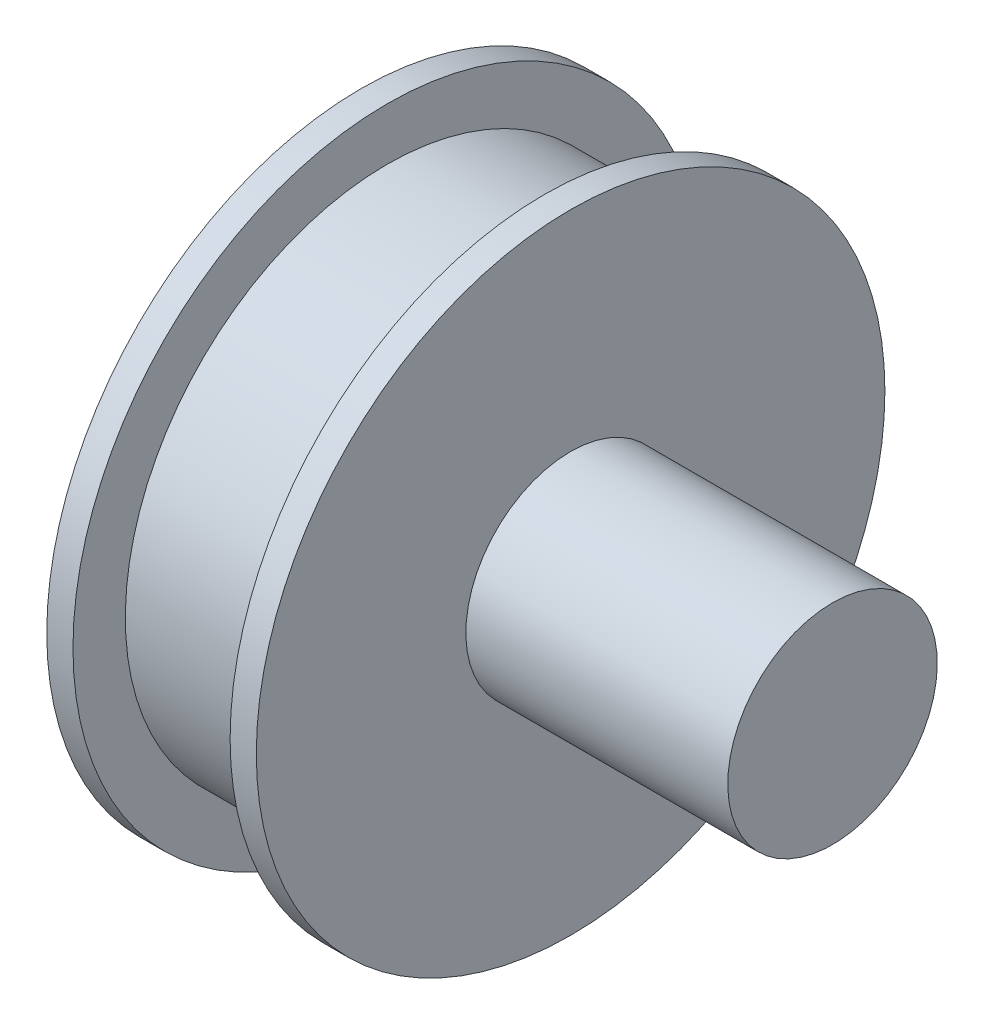
SolidWorks part; units mm, degrees
material "Plain Carbon Steel"
ref_plane "Front Plane" through (0, 0, 0) normal (0, 0, 1) x (1, 0, 0)
ref_plane "Top Plane" through (0, 0, 0) normal (0, 1, 0) x (1, 0, 0)
ref_plane "Right Plane" through (0, 0, 0) normal (1, 0, 0) x (0, 0, -1)
sketch "Sketch1" plane through (0, 0, 0) normal (0, 0, 1) x (1, 0, 0)
  line L0 (0, 5) -> (0, 30)
  line L1 (0, 30) -> (2.5, 30)
  line L2 (2.5, 30) -> (2.5, 25)
  line L3 (2.5, 25) -> (17.5, 25)
  line L4 (17.5, 25) -> (17.5, 30)
  line L5 (17.5, 30) -> (20, 30)
  line L6 (20, 30) -> (20, 10)
  line L7 (20, 10) -> (45, 10)
  line L8 (45, 10) -> (45, 0)
  line L9 (45, 0) -> (5, 0)
  line L10 (0, 5) -> (5, 5)
  line L11 (5, 5) -> (5, 0)
  point P0 (0, 0)
  dimension "D2" = 2.5
  dimension "D3" = 15
  dimension "D4" = 2.5
  dimension "D6" = 10
  dimension "D7" = 30
  dimension "D8" = 5
  dimension "D9" = 5
revolve "Revolve1" add sketch "Sketch1" angle 360 about L9
sketch "Sketch2" plane through (0, 0, 0) normal (-1, 0, 0) x (0, 0, 1)
  circle A0 centre (0, 0) radius 22.5
  circle A1 centre (0, 0) radius 10
  dimension "D1" = 45
  dimension "D2" = 20
extrude "Cut-Extrude1" cut sketch "Sketch2" against normal blind 5
fillet "Fillet1" radius 1 1 edges at (0, -10, 0)
